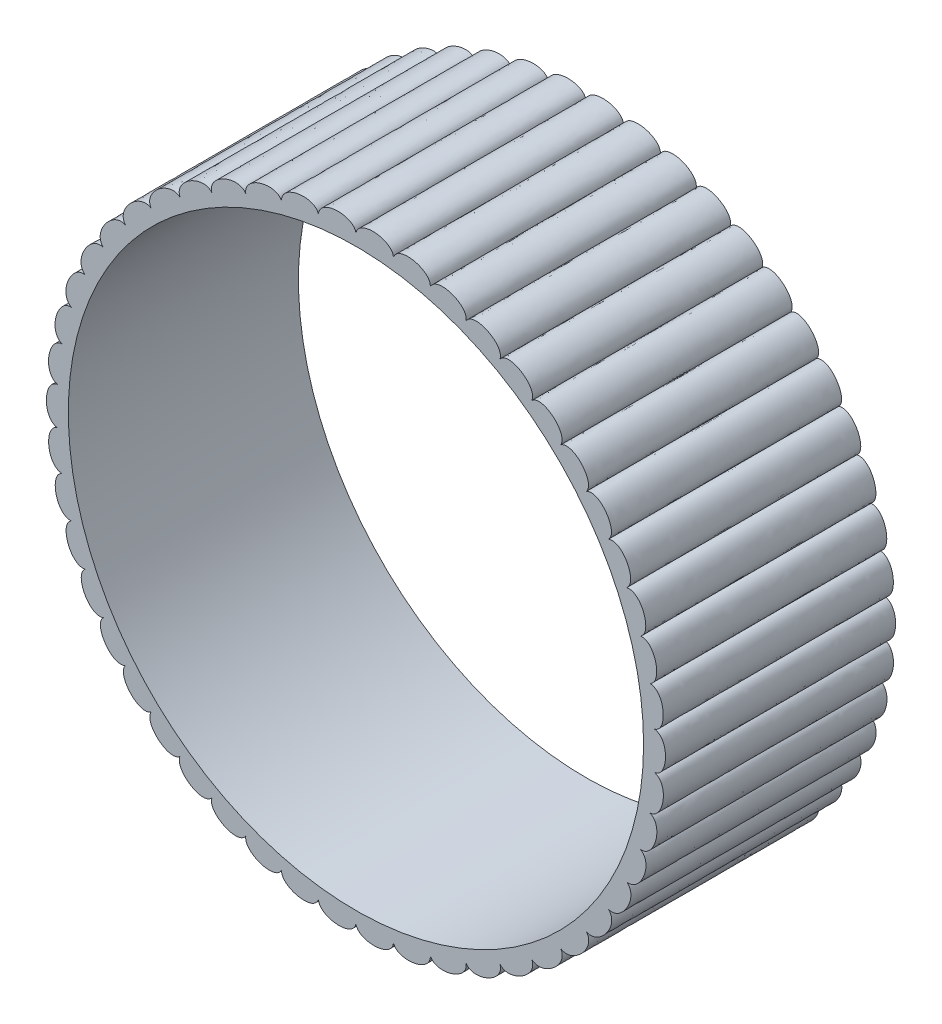
SolidWorks part; units mm, degrees
ref_plane "Front Plane" through (0, 0, 0) normal (0, 0, 1) x (1, 0, 0)
ref_plane "Top Plane" through (0, 0, 0) normal (0, 1, 0) x (1, 0, 0)
ref_plane "Right Plane" through (0, 0, 0) normal (1, 0, 0) x (0, 0, -1)
sketch "Sketch1" plane through (0, 0, 0) normal (0, 0, 1) x (1, 0, 0)
  line L0 (0, 0) -> (0, 26) construction
  line L1 (0, 0) -> (1.6326, 25.9487) construction
  line L2 (0, 0) -> (3.2587, 25.795) construction
  line L3 (0, 0) -> (4.8719, 25.5395) construction
  line L4 (0, 0) -> (6.4659, 25.1832) construction
  line L5 (0, 0) -> (8.0344, 24.7275) construction
  line L6 (0, 0) -> (9.5712, 24.1742) construction
  line L7 (0, 0) -> (11.0703, 23.5255) construction
  line L8 (0, 0) -> (12.5256, 22.784) construction
  line L9 (0, 0) -> (13.9315, 21.9525) construction
  line L10 (0, 0) -> (15.2824, 21.0344) construction
  line L11 (0, 0) -> (16.573, 20.0333) construction
  line L12 (0, 0) -> (17.7982, 18.9532) construction
  line L13 (0, 0) -> (18.9532, 17.7982) construction
  line L14 (0, 0) -> (20.0333, 16.573) construction
  line L15 (0, 0) -> (21.0344, 15.2824) construction
  line L16 (0, 0) -> (21.9525, 13.9315) construction
  line L17 (0, 0) -> (22.784, 12.5256) construction
  line L18 (0, 0) -> (23.5255, 11.0703) construction
  line L19 (0, 0) -> (24.1742, 9.5712) construction
  line L20 (0, 0) -> (24.7275, 8.0344) construction
  line L21 (0, 0) -> (25.1832, 6.4659) construction
  line L22 (0, 0) -> (25.5395, 4.8719) construction
  line L23 (0, 0) -> (25.795, 3.2587) construction
  line L24 (0, 0) -> (25.9487, 1.6326) construction
  line L25 (0, 0) -> (26, 0) construction
  line L26 (0, 0) -> (25.9487, -1.6326) construction
  line L27 (0, 0) -> (25.795, -3.2587) construction
  line L28 (0, 0) -> (25.5395, -4.8719) construction
  line L29 (0, 0) -> (25.1832, -6.4659) construction
  line L30 (0, 0) -> (24.7275, -8.0344) construction
  line L31 (0, 0) -> (24.1742, -9.5712) construction
  line L32 (0, 0) -> (23.5255, -11.0703) construction
  line L33 (0, 0) -> (22.784, -12.5256) construction
  line L34 (0, 0) -> (21.9525, -13.9315) construction
  line L35 (0, 0) -> (21.0344, -15.2824) construction
  line L36 (0, 0) -> (20.0333, -16.573) construction
  line L37 (0, 0) -> (18.9532, -17.7982) construction
  line L38 (0, 0) -> (17.7982, -18.9532) construction
  line L39 (0, 0) -> (16.573, -20.0333) construction
  line L40 (0, 0) -> (15.2824, -21.0344) construction
  line L41 (0, 0) -> (13.9315, -21.9525) construction
  line L42 (0, 0) -> (12.5256, -22.784) construction
  line L43 (0, 0) -> (11.0703, -23.5255) construction
  line L44 (0, 0) -> (9.5712, -24.1742) construction
  line L45 (0, 0) -> (8.0344, -24.7275) construction
  line L46 (0, 0) -> (6.4659, -25.1832) construction
  line L47 (0, 0) -> (4.8719, -25.5395) construction
  line L48 (0, 0) -> (3.2587, -25.795) construction
  line L49 (0, 0) -> (1.6326, -25.9487) construction
  line L50 (0, 26) -> (0, 28.397) construction
  line L51 (1.4985, 23.8176) -> (1.8054, 28.6959) construction
  line L52 (0, 0) -> (0, -26) construction
  line L53 (0, 0) -> (-1.6326, -25.9487) construction
  line L54 (0, 0) -> (-3.2587, -25.795) construction
  line L55 (0, 0) -> (-4.8719, -25.5395) construction
  line L56 (0, 0) -> (-6.4659, -25.1832) construction
  line L57 (0, 0) -> (-8.0344, -24.7275) construction
  line L58 (0, 0) -> (-9.5712, -24.1742) construction
  line L59 (0, 0) -> (-11.0703, -23.5255) construction
  line L60 (0, 0) -> (-12.5256, -22.784) construction
  line L61 (0, 0) -> (-13.9315, -21.9525) construction
  line L62 (0, 0) -> (-15.2824, -21.0344) construction
  line L63 (0, 0) -> (-16.573, -20.0333) construction
  line L64 (0, 0) -> (-17.7982, -18.9532) construction
  line L65 (0, 0) -> (-18.9532, -17.7982) construction
  line L66 (0, 0) -> (-20.0333, -16.573) construction
  line L67 (0, 0) -> (-21.0344, -15.2824) construction
  line L68 (0, 0) -> (-21.9525, -13.9315) construction
  line L69 (0, 0) -> (-22.784, -12.5256) construction
  line L70 (0, 0) -> (-23.5255, -11.0703) construction
  line L71 (0, 0) -> (-24.1742, -9.5712) construction
  line L72 (0, 0) -> (-24.7275, -8.0344) construction
  line L73 (0, 0) -> (-25.1832, -6.4659) construction
  line L74 (0, 0) -> (-25.5395, -4.8719) construction
  line L75 (0, 0) -> (-25.795, -3.2587) construction
  line L76 (0, 0) -> (-25.9487, -1.6326) construction
  line L77 (0, 0) -> (-26, 0) construction
  line L78 (0, 0) -> (-25.9487, 1.6326) construction
  line L79 (0, 0) -> (-25.795, 3.2587) construction
  line L80 (0, 0) -> (-25.5395, 4.8719) construction
  line L81 (0, 0) -> (-25.1832, 6.4659) construction
  line L82 (0, 0) -> (-24.7275, 8.0344) construction
  line L83 (0, 0) -> (-24.1742, 9.5712) construction
  line L84 (0, 0) -> (-23.5255, 11.0703) construction
  line L85 (0, 0) -> (-22.784, 12.5256) construction
  line L86 (0, 0) -> (-21.9525, 13.9315) construction
  line L87 (0, 0) -> (-21.0344, 15.2824) construction
  line L88 (0, 0) -> (-20.0333, 16.573) construction
  line L89 (0, 0) -> (-18.9532, 17.7982) construction
  line L90 (0, 0) -> (-17.7982, 18.9532) construction
  line L91 (0, 0) -> (-16.573, 20.0333) construction
  line L92 (0, 0) -> (-15.2824, 21.0344) construction
  line L93 (0, 0) -> (-13.9315, 21.9525) construction
  line L94 (0, 0) -> (-12.5256, 22.784) construction
  line L95 (0, 0) -> (-11.0703, 23.5255) construction
  line L96 (0, 0) -> (-9.5712, 24.1742) construction
  line L97 (0, 0) -> (-8.0344, 24.7275) construction
  line L98 (0, 0) -> (-6.4659, 25.1832) construction
  line L99 (0, 0) -> (-4.8719, 25.5395) construction
  line L100 (0, 0) -> (-3.2587, 25.795) construction
  line L101 (0, 0) -> (-1.6326, 25.9487) construction
  circle A0 centre (0, 0) radius 25
  arc A1 (0, 26) -> (12.5256, 22.784) centre (0, 0) ccw construction
  circle A2 centre (0, 0) radius 26 construction
  spline S0 degree 3 poles (0, 26) (0.1239, 26.6202) (0.985, 26.9152) (2.4397, 26.7945) (3.2112, 26.3803) (3.2587, 25.795) knots 0 0 0 0 0.438491 0.538491 1 1 1 1
  spline S1 degree 3 poles (3.2587, 25.795) (3.4593, 26.3948) (4.3506, 26.5795) (5.7787, 26.2775) (6.4923, 25.7698) (6.4659, 25.1832) knots 0 0 0 0 0.438491 0.538491 1 1 1 1
  spline S2 degree 3 poles (6.4659, 25.1832) (6.7402, 25.7531) (7.6476, 25.8246) (9.0265, 25.346) (9.6709, 24.7529) (9.5712, 24.1742) knots 0 0 0 0 0.438491 0.538491 1 1 1 1
  spline S3 degree 3 poles (9.5712, 24.1742) (9.9148, 24.7052) (10.824, 24.6625) (12.1321, 24.0148) (12.697, 23.3457) (12.5256, 22.784) knots 0 0 0 0 0.438491 0.538491 1 1 1 1
  spline S4 degree 3 poles (12.5256, 22.784) (12.933, 23.2678) (13.8297, 23.1114) (15.0463, 22.3049) (15.5229, 21.5702) (15.2824, 21.0344) knots 0 0 0 0 0.438491 0.538491 1 1 1 1
  spline S5 degree 3 poles (15.2824, 21.0344) (15.7472, 21.4634) (16.6173, 21.1959) (17.7232, 20.2432) (18.1039, 19.4546) (17.7982, 18.9532) knots 0 0 0 0 0.438491 0.538491 1 1 1 1
  spline S6 degree 3 poles (17.7982, 18.9532) (18.3131, 19.3205) (19.1428, 18.946) (20.1206, 17.8623) (20.3995, 17.0322) (20.0333, 16.573) knots 0 0 0 0 0.438491 0.538491 1 1 1 1
  spline S7 degree 3 poles (20.0333, 16.573) (20.5902, 16.8729) (21.3664, 16.3974) (22.2006, 15.1997) (22.3733, 14.3411) (21.9525, 13.9315) knots 0 0 0 0 0.438491 0.538491 1 1 1 1
  spline S8 degree 3 poles (21.9525, 13.9315) (22.5426, 14.1592) (23.2531, 13.5902) (23.9306, 12.2974) (23.9943, 11.4239) (23.5255, 11.0703) knots 0 0 0 0 0.438491 0.538491 1 1 1 1
  spline S9 degree 3 poles (23.5255, 11.0703) (24.1395, 11.2222) (24.773, 10.5686) (25.2832, 9.2011) (25.2369, 8.3266) (24.7275, 8.0344) knots 0 0 0 0 0.438491 0.538491 1 1 1 1
  spline S10 degree 3 poles (24.7275, 8.0344) (25.3556, 8.1083) (25.9023, 7.3804) (26.237, 5.9597) (26.0815, 5.0979) (25.5395, 4.8719) knots 0 0 0 0 0.438491 0.538491 1 1 1 1
  spline S11 degree 3 poles (25.5395, 4.8719) (26.1719, 4.8664) (26.623, 4.0758) (26.7771, 2.6244) (26.5148, 1.7888) (25.9487, 1.6326) knots 0 0 0 0 0.438491 0.538491 1 1 1 1
  spline S12 degree 3 poles (25.9487, 1.6326) (26.5755, 1.5478) (26.9239, 0.7069) (26.8948, -0.7524) (26.5299, -1.5485) (25.9487, -1.6326) knots 0 0 0 0 0.438491 0.538491 1 1 1 1
  spline S13 degree 3 poles (25.9487, -1.6326) (26.5599, -1.7952) (26.8002, -2.6731) (26.5885, -4.1173) (26.1266, -4.8613) (25.5395, -4.8719) knots 0 0 0 0 0.438491 0.538491 1 1 1 1
  spline S14 degree 3 poles (25.5395, -4.8719) (26.1255, -5.1099) (26.2539, -6.011) (25.8628, -7.4172) (25.3113, -8.0976) (24.7275, -8.0344) knots 0 0 0 0 0.438491 0.538491 1 1 1 1
  spline S15 degree 3 poles (24.7275, -8.0344) (25.279, -8.344) (25.2935, -9.2541) (24.7292, -10.6002) (24.0969, -11.2061) (23.5255, -11.0703) knots 0 0 0 0 0.438491 0.538491 1 1 1 1
  spline S16 degree 3 poles (23.5255, -11.0703) (24.0339, -11.4465) (23.9342, -12.3512) (23.2057, -13.616) (22.5024, -14.1378) (21.9525, -13.9315) knots 0 0 0 0 0.438491 0.538491 1 1 1 1
  spline S17 degree 3 poles (21.9525, -13.9315) (22.4098, -14.3685) (22.1974, -15.2536) (21.3161, -16.4171) (20.553, -16.8466) (20.0333, -16.573) knots 0 0 0 0 0.438491 0.538491 1 1 1 1
  spline S18 degree 3 poles (20.0333, -16.573) (20.4322, -17.0639) (20.1106, -17.9154) (19.0904, -18.9593) (18.2795, -19.2898) (17.7982, -18.9532) knots 0 0 0 0 0.438491 0.538491 1 1 1 1
  spline S19 degree 3 poles (17.7982, -18.9532) (18.1325, -19.4901) (17.7067, -20.2946) (16.5637, -21.2024) (15.7177, -21.4287) (15.2824, -21.0344) knots 0 0 0 0 0.438491 0.538491 1 1 1 1
  spline S20 degree 3 poles (15.2824, -21.0344) (15.5467, -21.6091) (15.0234, -22.3538) (13.7757, -23.1112) (12.908, -23.2297) (12.5256, -22.784) knots 0 0 0 0 0.438491 0.538491 1 1 1 1
  spline S21 degree 3 poles (12.5256, -22.784) (12.7158, -23.3872) (12.1033, -24.0605) (10.7705, -24.6555) (9.8948, -24.6643) (9.5712, -24.1742) knots 0 0 0 0 0.438491 0.538491 1 1 1 1
  spline S22 degree 3 poles (9.5712, -24.1742) (9.6843, -24.7965) (8.9923, -25.3877) (7.5954, -25.811) (6.7255, -25.71) (6.4659, -25.1832) knots 0 0 0 0 0.438491 0.538491 1 1 1 1
  spline S23 degree 3 poles (6.4659, -25.1832) (6.5002, -25.8147) (5.7395, -26.3146) (4.3005, -26.5594) (3.4502, -26.3502) (3.2587, -25.795) knots 0 0 0 0 0.438491 0.538491 1 1 1 1
  spline S24 degree 3 poles (3.2587, -25.795) (3.2135, -26.4258) (2.3961, -26.8264) (0.9378, -26.889) (0.1204, -26.5748) (0, -26) knots 0 0 0 0 0.438491 0.538491 1 1 1 1
  spline S25 degree 3 poles (0, -26) (-0.1239, -26.6202) (-0.985, -26.9152) (-2.4397, -26.7945) (-3.2112, -26.3803) (-3.2587, -25.795) knots 0 0 0 0 0.438491 0.538491 1 1 1 1
  spline S26 degree 3 poles (-3.2587, -25.795) (-3.4593, -26.3948) (-4.3506, -26.5795) (-5.7787, -26.2775) (-6.4923, -25.7698) (-6.4659, -25.1832) knots 0 0 0 0 0.438491 0.538491 1 1 1 1
  spline S27 degree 3 poles (-6.4659, -25.1832) (-6.7402, -25.7531) (-7.6476, -25.8246) (-9.0265, -25.346) (-9.6709, -24.7529) (-9.5712, -24.1742) knots 0 0 0 0 0.438491 0.538491 1 1 1 1
  spline S28 degree 3 poles (-9.5712, -24.1742) (-9.9148, -24.7052) (-10.824, -24.6625) (-12.1321, -24.0148) (-12.697, -23.3457) (-12.5256, -22.784) knots 0 0 0 0 0.438491 0.538491 1 1 1 1
  spline S29 degree 3 poles (-12.5256, -22.784) (-12.933, -23.2678) (-13.8297, -23.1114) (-15.0463, -22.3049) (-15.5229, -21.5702) (-15.2824, -21.0344) knots 0 0 0 0 0.438491 0.538491 1 1 1 1
  spline S30 degree 3 poles (-15.2824, -21.0344) (-15.7472, -21.4634) (-16.6173, -21.1959) (-17.7232, -20.2432) (-18.1039, -19.4546) (-17.7982, -18.9532) knots 0 0 0 0 0.438491 0.538491 1 1 1 1
  spline S31 degree 3 poles (-17.7982, -18.9532) (-18.3131, -19.3205) (-19.1428, -18.946) (-20.1206, -17.8623) (-20.3995, -17.0322) (-20.0333, -16.573) knots 0 0 0 0 0.438491 0.538491 1 1 1 1
  spline S32 degree 3 poles (-20.0333, -16.573) (-20.5902, -16.8729) (-21.3664, -16.3974) (-22.2006, -15.1997) (-22.3733, -14.3411) (-21.9525, -13.9315) knots 0 0 0 0 0.438491 0.538491 1 1 1 1
  spline S33 degree 3 poles (-21.9525, -13.9315) (-22.5426, -14.1592) (-23.2531, -13.5902) (-23.9306, -12.2974) (-23.9943, -11.4239) (-23.5255, -11.0703) knots 0 0 0 0 0.438491 0.538491 1 1 1 1
  spline S34 degree 3 poles (-23.5255, -11.0703) (-24.1395, -11.2222) (-24.773, -10.5686) (-25.2832, -9.2011) (-25.2369, -8.3266) (-24.7275, -8.0344) knots 0 0 0 0 0.438491 0.538491 1 1 1 1
  spline S35 degree 3 poles (-24.7275, -8.0344) (-25.3556, -8.1083) (-25.9023, -7.3804) (-26.237, -5.9597) (-26.0815, -5.0979) (-25.5395, -4.8719) knots 0 0 0 0 0.438491 0.538491 1 1 1 1
  spline S36 degree 3 poles (-25.5395, -4.8719) (-26.1719, -4.8664) (-26.623, -4.0758) (-26.7771, -2.6244) (-26.5148, -1.7888) (-25.9487, -1.6326) knots 0 0 0 0 0.438491 0.538491 1 1 1 1
  spline S37 degree 3 poles (-25.9487, -1.6326) (-26.5755, -1.5478) (-26.9239, -0.7069) (-26.8948, 0.7524) (-26.5299, 1.5485) (-25.9487, 1.6326) knots 0 0 0 0 0.438491 0.538491 1 1 1 1
  spline S38 degree 3 poles (-25.9487, 1.6326) (-26.5599, 1.7952) (-26.8002, 2.6731) (-26.5885, 4.1173) (-26.1266, 4.8613) (-25.5395, 4.8719) knots 0 0 0 0 0.438491 0.538491 1 1 1 1
  spline S39 degree 3 poles (-25.5395, 4.8719) (-26.1255, 5.1099) (-26.2539, 6.011) (-25.8628, 7.4172) (-25.3113, 8.0976) (-24.7275, 8.0344) knots 0 0 0 0 0.438491 0.538491 1 1 1 1
  spline S40 degree 3 poles (-24.7275, 8.0344) (-25.279, 8.344) (-25.2935, 9.2541) (-24.7292, 10.6002) (-24.0969, 11.2061) (-23.5255, 11.0703) knots 0 0 0 0 0.438491 0.538491 1 1 1 1
  spline S41 degree 3 poles (-23.5255, 11.0703) (-24.0339, 11.4465) (-23.9342, 12.3512) (-23.2057, 13.616) (-22.5024, 14.1378) (-21.9525, 13.9315) knots 0 0 0 0 0.438491 0.538491 1 1 1 1
  spline S42 degree 3 poles (-21.9525, 13.9315) (-22.4098, 14.3685) (-22.1974, 15.2536) (-21.3161, 16.4171) (-20.553, 16.8466) (-20.0333, 16.573) knots 0 0 0 0 0.438491 0.538491 1 1 1 1
  spline S43 degree 3 poles (-20.0333, 16.573) (-20.4322, 17.0639) (-20.1106, 17.9154) (-19.0904, 18.9593) (-18.2795, 19.2898) (-17.7982, 18.9532) knots 0 0 0 0 0.438491 0.538491 1 1 1 1
  spline S44 degree 3 poles (-17.7982, 18.9532) (-18.1325, 19.4901) (-17.7067, 20.2946) (-16.5637, 21.2024) (-15.7177, 21.4287) (-15.2824, 21.0344) knots 0 0 0 0 0.438491 0.538491 1 1 1 1
  spline S45 degree 3 poles (-15.2824, 21.0344) (-15.5467, 21.6091) (-15.0234, 22.3538) (-13.7757, 23.1112) (-12.908, 23.2297) (-12.5256, 22.784) knots 0 0 0 0 0.438491 0.538491 1 1 1 1
  spline S46 degree 3 poles (-12.5256, 22.784) (-12.7158, 23.3872) (-12.1033, 24.0605) (-10.7705, 24.6555) (-9.8948, 24.6643) (-9.5712, 24.1742) knots 0 0 0 0 0.438491 0.538491 1 1 1 1
  spline S47 degree 3 poles (-9.5712, 24.1742) (-9.6843, 24.7965) (-8.9923, 25.3877) (-7.5954, 25.811) (-6.7255, 25.71) (-6.4659, 25.1832) knots 0 0 0 0 0.438491 0.538491 1 1 1 1
  spline S48 degree 3 poles (-6.4659, 25.1832) (-6.5002, 25.8147) (-5.7395, 26.3146) (-4.3005, 26.5594) (-3.4502, 26.3502) (-3.2587, 25.795) knots 0 0 0 0 0.438491 0.538491 1 1 1 1
  spline S49 degree 3 poles (-3.2587, 25.795) (-3.2135, 26.4258) (-2.3961, 26.8264) (-0.9378, 26.889) (-0.1204, 26.5748) (0, 26) knots 0 0 0 0 0.438491 0.538491 1 1 1 1
  dimension "D1" = 50
  dimension "D3" = 100
  dimension "D2" = 1
extrude "Boss-Extrude1" add sketch "Sketch1" along normal blind 20 contours S49 S48 S47 S46 S45 S44 S43 S42 S41 S40 S39 S38 S37 S36 S35 S34 S33 S32 S31 S30 S29 S28 S27 S26 S25 S24 S23 S22 S21 S20 S19 S18 S17 S16 S15 S14 S13 S12 S11 S10 S9 S8 S7 S6 S5 S4 S3 S2 S1 S0
